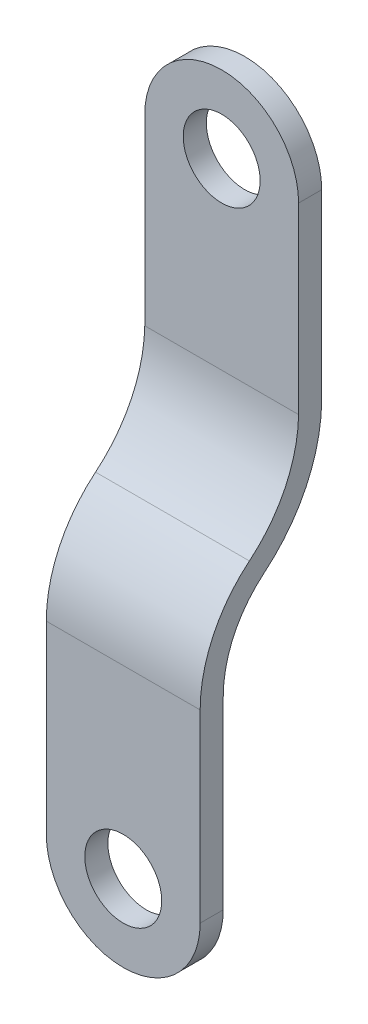
SolidWorks part; units mm, degrees
ref_plane "Front Plane" through (0, 0, 0) normal (0, 0, 1) x (1, 0, 0)
ref_plane "Top Plane" through (0, 0, 0) normal (0, 1, 0) x (1, 0, 0)
ref_plane "Right Plane" through (0, 0, 0) normal (1, 0, 0) x (0, 0, -1)
sketch "Sketch2" plane through (0, 0, 0) normal (0, 0, 1) x (1, 0, 0)
  line L0 (0, 0) -> (0, 37.3344) construction
  line L1 (0, 0) -> (105.8668, 18.6672) construction
  line L2 (0, 37.3344) -> (105.8668, 18.6672) construction
  line L3 (-5, 37.3344) -> (-5, 0)
  line L4 (5, 37.3344) -> (5, 0)
  circle A0 centre (0, 37.3344) radius 5
  circle A1 centre (0, 0) radius 5
  dimension "D4" = 10
  dimension "D1" = 107.5
  dimension "D2" = 20
  dimension "D3" = 37.3344
sketch "Sketch4" plane through (0, 0, 0) normal (1, 0, 0) x (0, 0, -1)
  line L1 (1.5, 0) -> (1.5, 12)
  line L4 (6.3987, 37.3344) -> (7.8987, 37.3344)
  line L8 (1.5, 0) -> (0, 0)
  line L9 (0, 0) -> (0, 12)
  line L10 (6.3987, 25.4257) -> (6.3987, 37.3344)
  line L11 (7.8987, 25.4136) -> (7.8987, 37.3344)
  line L12 (1.5, 0) -> (1.5, 12) construction
  arc A0 (0, 12) -> (3.2, 18.787) centre (8.7974, 12) cw
  arc A1 (3.2, 18.787) -> (6.3987, 25.4257) centre (-2.3974, 25.574) ccw
  arc A2 (1.5, 12) -> (4.1544, 17.6298) centre (8.7974, 12) cw
  arc A3 (4.1544, 17.6298) -> (7.8987, 25.4136) centre (-2.3974, 25.574) ccw
  dimension "D7" = 1.5
  dimension "D1" = 37.3344
  dimension "D2" = 1.5
  dimension "D3" = 18.787
  dimension "D4" = 12
  dimension "D5" = 6.3987
  dimension "D6" = 3.2
extrude "Bracket Base" add sketch "Sketch4" against normal mid plane 10
sketch "Sketch7" plane through (0, 0, 0) normal (0, 0, 1) x (1, 0, 0)
  circle A0 centre (0, 0) radius 5 construction
  circle A1 centre (0, 0) radius 5
extrude "Radius 1" add sketch "Sketch7" against normal up to surface (1.5 mm away) up to face at (0, 6, -1.5)
sketch "Sketch8" plane through (0, 0, -6.3987) normal (0, 0, 1) x (1, 0, 0)
  circle A0 centre (0, 37.3344) radius 5 construction
  circle A1 centre (0, 37.3344) radius 5
extrude "Radius 2" add sketch "Sketch8" against normal up to surface (1.5 mm away) up to face at (0, 31.374, -7.8987)
sketch "Sketch9" plane through (0, 0, 0) normal (0, 0, 1) x (1, 0, 0)
  circle A0 centre (0, 0) radius 2.5
  circle A1 centre (0, 37.3344) radius 2.5
  dimension "D1" = 5
extrude "Holes" cut sketch "Sketch9" against normal through all
equation "\"a\"= 1"
equation "\"b\"= 1"
equation "\"c\"= 1"
equation "\"d\"= 1"
equation "\"e\"= 1"
equation "\"x\"= 1"
equation "\"y\"= 1"
equation "\"z\"= 1"
equation "\"D1@Sketch2\"=215/2"
